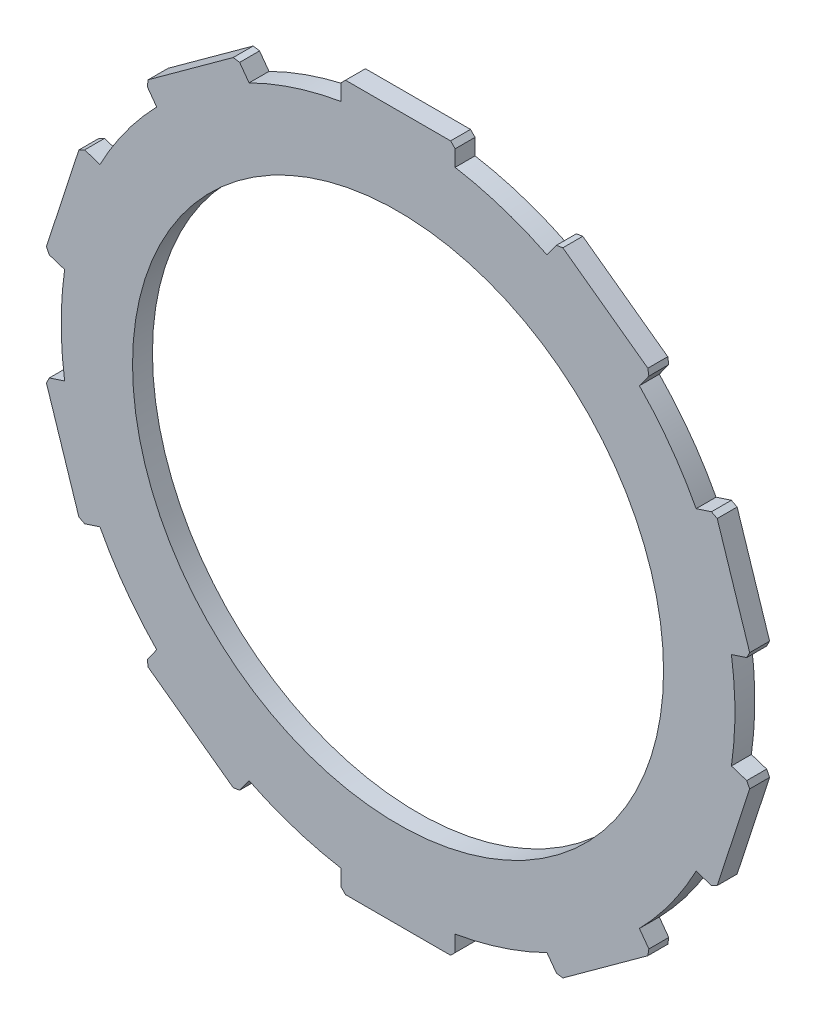
SolidWorks part; units mm, degrees
material "Oak"
ref_plane "Front Plane" through (0, 0, 0) normal (0, 0, 1) x (1, 0, 0)
ref_plane "Top Plane" through (0, 0, 0) normal (0, 1, 0) x (1, 0, 0)
ref_plane "Right Plane" through (0, 0, 0) normal (1, 0, 0) x (0, 0, -1)
sketch "Base_Sketch" plane through (0, 0, 0) normal (0, 0, 1) x (1, 0, 0)
  line L0 (0, 13.5203) -> (0, -9.6246) construction
  line L1 (-15.6973, 0) -> (7.1726, 0) construction
  line L2 (-7.854, 49.3793) -> (-7.854, 52.1293)
  line L3 (-7.604, 52.3793) -> (7.604, 52.3793)
  line L4 (7.854, 52.1293) -> (7.854, 49.3793)
  line L5 (-7.854, 52.1293) -> (-7.604, 52.3793)
  line L6 (7.604, 52.3793) -> (7.854, 52.1293)
  line L7 (-7.854, 52.3793) -> (-7.604, 52.3793) construction
  line L8 (7.604, 52.3793) -> (7.854, 52.3793) construction
  line L9 (-7.854, 52.3793) -> (-7.854, 52.1293) construction
  line L10 (7.854, 52.1293) -> (7.854, 52.3793) construction
  line L11 (-7.854, 49.3793) -> (7.854, 49.3793) construction
  line L12 (22.6704, 44.5651) -> (24.2868, 46.7899)
  line L13 (24.636, 46.8452) -> (36.9395, 37.9062)
  line L14 (24.2868, 46.7899) -> (24.636, 46.8452)
  line L15 (36.9395, 37.9062) -> (36.9948, 37.557)
  line L16 (36.9948, 37.557) -> (35.3784, 35.3322)
  line L17 (22.6704, 44.5651) -> (35.3784, 35.3322) construction
  line L18 (44.5355, 22.7286) -> (47.1509, 23.5784)
  line L19 (47.4659, 23.4179) -> (52.1654, 8.9543)
  line L20 (47.1509, 23.5784) -> (47.4659, 23.4179)
  line L21 (52.1654, 8.9543) -> (52.0049, 8.6393)
  line L22 (52.0049, 8.6393) -> (49.3895, 7.7895)
  line L23 (44.5355, 22.7286) -> (49.3895, 7.7895) construction
  line L24 (49.3895, -7.7895) -> (52.0049, -8.6393)
  line L25 (52.1654, -8.9543) -> (47.4659, -23.4179)
  line L26 (52.0049, -8.6393) -> (52.1654, -8.9543)
  line L27 (47.4659, -23.4179) -> (47.1509, -23.5784)
  line L28 (47.1509, -23.5784) -> (44.5355, -22.7286)
  line L29 (49.3895, -7.7895) -> (44.5355, -22.7286) construction
  line L30 (0, 0) -> (15.4508, 47.5528) construction
  line L31 (0, 0) -> (40.4508, 29.3893) construction
  line L32 (35.3784, -35.3322) -> (36.9948, -37.557)
  line L33 (36.9395, -37.9062) -> (24.636, -46.8452)
  line L34 (36.9948, -37.557) -> (36.9395, -37.9062)
  line L35 (24.636, -46.8452) -> (24.2868, -46.7899)
  line L36 (24.2868, -46.7899) -> (22.6704, -44.5651)
  line L37 (35.3784, -35.3322) -> (22.6704, -44.5651) construction
  line L38 (7.854, -49.3793) -> (7.854, -52.1293)
  line L39 (7.604, -52.3793) -> (-7.604, -52.3793)
  line L40 (7.854, -52.1293) -> (7.604, -52.3793)
  line L41 (-7.604, -52.3793) -> (-7.854, -52.1293)
  line L42 (-7.854, -52.1293) -> (-7.854, -49.3793)
  line L43 (7.854, -49.3793) -> (-7.854, -49.3793) construction
  line L44 (-22.6704, -44.5651) -> (-24.2868, -46.7899)
  line L45 (-24.636, -46.8452) -> (-36.9395, -37.9062)
  line L46 (-24.2868, -46.7899) -> (-24.636, -46.8452)
  line L47 (-36.9395, -37.9062) -> (-36.9948, -37.557)
  line L48 (-36.9948, -37.557) -> (-35.3784, -35.3322)
  line L49 (-22.6704, -44.5651) -> (-35.3784, -35.3322) construction
  line L50 (-44.5355, -22.7286) -> (-47.1509, -23.5784)
  line L51 (-47.4659, -23.4179) -> (-52.1654, -8.9543)
  line L52 (-47.1509, -23.5784) -> (-47.4659, -23.4179)
  line L53 (-52.1654, -8.9543) -> (-52.0049, -8.6393)
  line L54 (-52.0049, -8.6393) -> (-49.3895, -7.7895)
  line L55 (-44.5355, -22.7286) -> (-49.3895, -7.7895) construction
  line L56 (-49.3895, 7.7895) -> (-52.0049, 8.6393)
  line L57 (-52.1654, 8.9543) -> (-47.4659, 23.4179)
  line L58 (-52.0049, 8.6393) -> (-52.1654, 8.9543)
  line L59 (-47.4659, 23.4179) -> (-47.1509, 23.5784)
  line L60 (-47.1509, 23.5784) -> (-44.5355, 22.7286)
  line L61 (-49.3895, 7.7895) -> (-44.5355, 22.7286) construction
  line L62 (-35.3784, 35.3322) -> (-36.9948, 37.557)
  line L63 (-36.9395, 37.9062) -> (-24.636, 46.8452)
  line L64 (-36.9948, 37.557) -> (-36.9395, 37.9062)
  line L65 (-24.636, 46.8452) -> (-24.2868, 46.7899)
  line L66 (-24.2868, 46.7899) -> (-22.6704, 44.5651)
  line L67 (-35.3784, 35.3322) -> (-22.6704, 44.5651) construction
  line L152 (-8.604, 50.0153) -> (-8.604, 52.44)
  line L153 (-8.604, 52.44) -> (-7.9146, 53.1293)
  line L154 (-7.9146, 53.1293) -> (7.9146, 53.1293)
  line L155 (7.9146, 53.1293) -> (8.604, 52.44)
  line L156 (8.604, 52.44) -> (8.604, 50.0153)
  line L157 (24.8255, 47.6346) -> (37.6317, 38.3304)
  line L158 (23.8627, 47.4821) -> (24.8255, 47.6346)
  line L159 (22.4375, 45.5206) -> (23.8627, 47.4821)
  line L160 (37.6317, 38.3304) -> (37.7842, 37.3675)
  line L161 (37.7842, 37.3675) -> (36.359, 35.406)
  line L162 (48.0832, 23.9451) -> (52.9747, 8.8906)
  line L163 (47.2146, 24.3877) -> (48.0832, 23.9451)
  line L164 (44.9086, 23.6385) -> (47.2146, 24.3877)
  line L165 (52.9747, 8.8906) -> (52.5321, 8.022)
  line L166 (52.5321, 8.022) -> (50.2262, 7.2727)
  line L167 (52.9747, -8.8906) -> (48.0832, -23.9451)
  line L168 (52.5321, -8.022) -> (52.9747, -8.8906)
  line L169 (50.2262, -7.2727) -> (52.5321, -8.022)
  line L170 (48.0832, -23.9451) -> (47.2146, -24.3877)
  line L171 (47.2146, -24.3877) -> (44.9086, -23.6385)
  line L172 (37.6317, -38.3304) -> (24.8255, -47.6346)
  line L173 (37.7842, -37.3675) -> (37.6317, -38.3304)
  line L174 (36.359, -35.406) -> (37.7842, -37.3675)
  line L175 (24.8255, -47.6346) -> (23.8627, -47.4821)
  line L176 (23.8627, -47.4821) -> (22.4375, -45.5206)
  line L177 (7.9146, -53.1293) -> (-7.9146, -53.1293)
  line L178 (8.604, -52.44) -> (7.9146, -53.1293)
  line L179 (8.604, -50.0153) -> (8.604, -52.44)
  line L180 (-7.9146, -53.1293) -> (-8.604, -52.44)
  line L181 (-8.604, -52.44) -> (-8.604, -50.0153)
  line L182 (-24.8255, -47.6346) -> (-37.6317, -38.3304)
  line L183 (-23.8627, -47.4821) -> (-24.8255, -47.6346)
  line L184 (-22.4375, -45.5206) -> (-23.8627, -47.4821)
  line L185 (-37.6317, -38.3304) -> (-37.7842, -37.3675)
  line L186 (-37.7842, -37.3675) -> (-36.359, -35.406)
  line L187 (-48.0832, -23.9451) -> (-52.9747, -8.8906)
  line L188 (-47.2146, -24.3877) -> (-48.0832, -23.9451)
  line L189 (-44.9086, -23.6385) -> (-47.2146, -24.3877)
  line L190 (-52.9747, -8.8906) -> (-52.5321, -8.022)
  line L191 (-52.5321, -8.022) -> (-50.2262, -7.2727)
  line L192 (-52.9747, 8.8906) -> (-48.0832, 23.9451)
  line L193 (-52.5321, 8.022) -> (-52.9747, 8.8906)
  line L194 (-50.2262, 7.2727) -> (-52.5321, 8.022)
  line L195 (-48.0832, 23.9451) -> (-47.2146, 24.3877)
  line L196 (-47.2146, 24.3877) -> (-44.9086, 23.6385)
  line L197 (-37.6317, 38.3304) -> (-24.8255, 47.6346)
  line L198 (-37.7842, 37.3675) -> (-37.6317, 38.3304)
  line L199 (-36.359, 35.406) -> (-37.7842, 37.3675)
  line L200 (-24.8255, 47.6346) -> (-23.8627, 47.4821)
  line L201 (-23.8627, 47.4821) -> (-22.4375, 45.5206)
  circle A0 centre (0, 0) radius 50 construction
  arc A1 (-7.854, 49.3793) -> (-15.4508, 47.5528) centre (0, 0) ccw
  arc A2 (15.4508, 47.5528) -> (7.854, 49.3793) centre (0, 0) ccw
  arc A3 (22.6704, 44.5651) -> (15.4508, 47.5528) centre (0, 0) ccw
  arc A4 (40.4508, 29.3893) -> (35.3784, 35.3322) centre (0, 0) ccw
  arc A5 (44.5355, 22.7286) -> (40.4508, 29.3893) centre (0, 0) ccw
  arc A6 (50, 0) -> (49.3895, 7.7895) centre (0, 0) ccw
  arc A7 (49.3895, -7.7895) -> (50, 0) centre (0, 0) ccw
  arc A8 (40.4508, -29.3893) -> (44.5355, -22.7286) centre (0, 0) ccw
  arc A9 (35.3784, -35.3322) -> (40.4508, -29.3893) centre (0, 0) ccw
  arc A10 (15.4508, -47.5528) -> (22.6704, -44.5651) centre (0, 0) ccw
  arc A11 (7.854, -49.3793) -> (15.4508, -47.5528) centre (0, 0) ccw
  arc A12 (-15.4508, -47.5528) -> (-7.854, -49.3793) centre (0, 0) ccw
  arc A13 (-22.6704, -44.5651) -> (-15.4508, -47.5528) centre (0, 0) ccw
  arc A14 (-40.4508, -29.3893) -> (-35.3784, -35.3322) centre (0, 0) ccw
  arc A15 (-44.5355, -22.7286) -> (-40.4508, -29.3893) centre (0, 0) ccw
  arc A16 (-50, 0) -> (-49.3895, -7.7895) centre (0, 0) ccw
  arc A17 (-49.3895, 7.7895) -> (-50, 0) centre (0, 0) ccw
  arc A18 (-40.4508, 29.3893) -> (-44.5355, 22.7286) centre (0, 0) ccw
  arc A19 (-35.3784, 35.3322) -> (-40.4508, 29.3893) centre (0, 0) ccw
  arc A20 (-15.4508, 47.5528) -> (-22.6704, 44.5651) centre (0, 0) ccw
  arc A49 (-8.604, 50.0153) -> (-15.6826, 48.2661) centre (0, 0) ccw
  arc A50 (15.6826, 48.2661) -> (8.604, 50.0153) centre (0, 0) ccw
  arc A51 (22.4375, 45.5206) -> (15.6826, 48.2661) centre (0, 0) ccw
  arc A52 (41.0576, 29.8301) -> (36.359, 35.406) centre (0, 0) ccw
  arc A53 (44.9086, 23.6385) -> (41.0576, 29.8301) centre (0, 0) ccw
  arc A54 (50.75, 0) -> (50.2262, 7.2727) centre (0, 0) ccw
  arc A55 (50.2262, -7.2727) -> (50.75, 0) centre (0, 0) ccw
  arc A56 (41.0576, -29.8301) -> (44.9086, -23.6385) centre (0, 0) ccw
  arc A57 (36.359, -35.406) -> (41.0576, -29.8301) centre (0, 0) ccw
  arc A58 (15.6826, -48.2661) -> (22.4375, -45.5206) centre (0, 0) ccw
  arc A59 (8.604, -50.0153) -> (15.6826, -48.2661) centre (0, 0) ccw
  arc A60 (-15.6826, -48.2661) -> (-8.604, -50.0153) centre (0, 0) ccw
  arc A61 (-22.4375, -45.5206) -> (-15.6826, -48.2661) centre (0, 0) ccw
  arc A62 (-41.0576, -29.8301) -> (-36.359, -35.406) centre (0, 0) ccw
  arc A63 (-44.9086, -23.6385) -> (-41.0576, -29.8301) centre (0, 0) ccw
  arc A64 (-50.75, 0) -> (-50.2262, -7.2727) centre (0, 0) ccw
  arc A65 (-50.2262, 7.2727) -> (-50.75, 0) centre (0, 0) ccw
  arc A66 (-41.0576, 29.8301) -> (-44.9086, 23.6385) centre (0, 0) ccw
  arc A67 (-36.359, 35.406) -> (-41.0576, 29.8301) centre (0, 0) ccw
  arc A68 (-15.6826, 48.2661) -> (-22.4375, 45.5206) centre (0, 0) ccw
  point P8 (-7.854, 52.3793)
  point P9 (7.854, 52.3793)
  point P241 (0, 0)
  dimension "D4" = 100
  dimension "D1" = 0.25
  dimension "D2" = 3
  dimension "D3" = 15.708
  dimension "D6" = 36
  dimension "D7" = 36
  dimension "D5" = 10
  dimension "D9" = 10
extrude "Boss-Extrude1" add sketch "Base_Sketch" along normal blind 3
sketch "Sketch1" plane through (0, 0, 0) normal (0, 0, -1) x (-1, 0, 0)
  circle A0 centre (0, 0) radius 40
  dimension "D1" = 80
extrude "Cut-Extrude1" cut sketch "Sketch1" against normal through all
equation "\"Material_Thickness\"= 3"
equation "\"D2@Base_Sketch\"=\"Material_Thickness\""
equation "\"Diameter\"= 100"
equation "\"Chamfer_Size\"= 0.25"
equation "\"Kerf\" = 0.75"
equation "\"D4@Base_Sketch\"=\"Diameter\""
equation "\"D3@Base_Sketch\" = ( \"Diameter\" * 3.14159265 ) / ( \"Num_Teeth\" * 2 )"
equation "\"Num_Teeth\"= 10"
equation "\"D7@Base_Sketch\"=360/(\"Num_Teeth\")"
equation "\"D5@Base_Sketch\"=\"Num_Teeth\""
equation "\"D8@Base_Sketch\"=\"Kerf\""
equation "\"D9@Base_Sketch\"=\"Num_Teeth\""
equation "\"D1@Boss-Extrude1\"=\"Material_Thickness\""
equation "\"Cover_Radius\"= 80"
equation "\"D1@Sketch1\"=\"Cover_Radius\""
